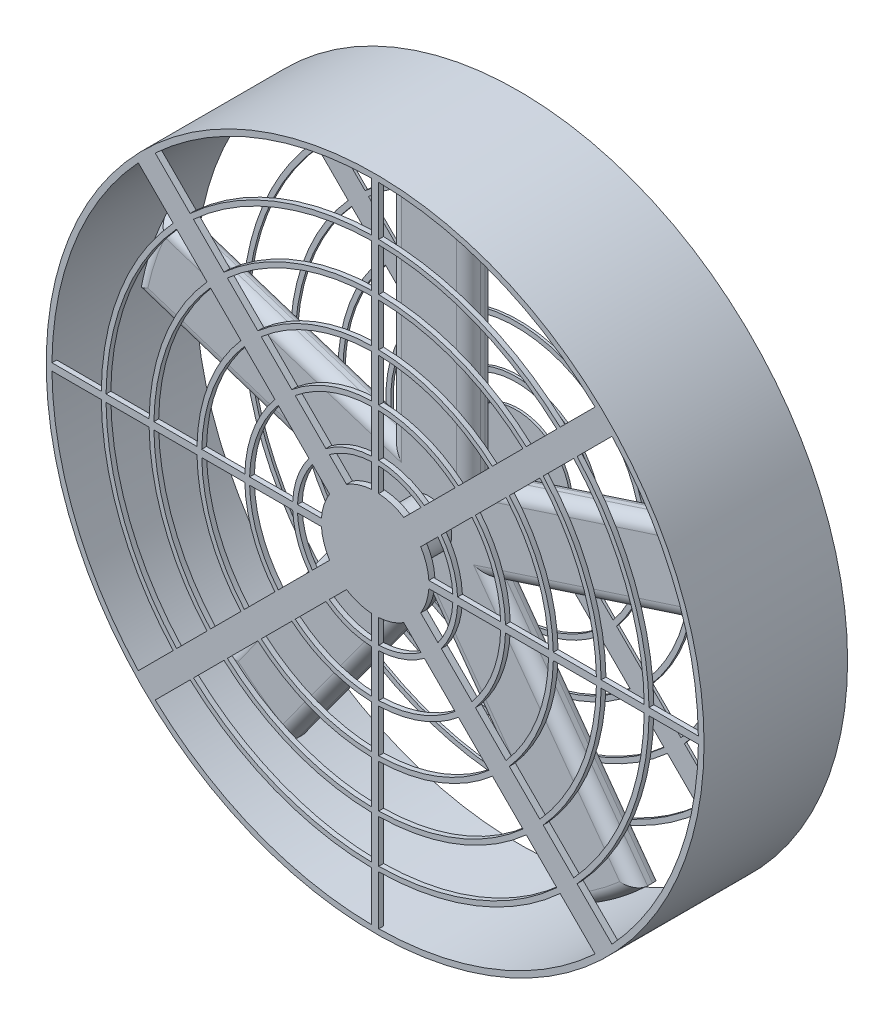
SolidWorks part; units mm, degrees
ref_plane "Alzado" through (0, 0, 0) normal (0, 0, 1) x (1, 0, 0)
ref_plane "Planta" through (0, 0, 0) normal (0, 1, 0) x (1, 0, 0)
ref_plane "Vista lateral" through (0, 0, 0) normal (1, 0, 0) x (0, 0, -1)
sketch "Croquis1" plane through (0, 0, 0) normal (0, 0, 1) x (1, 0, 0)
  circle A0 centre (0, 0) radius 275
  circle A1 centre (0, 0) radius 270.2375
  dimension "D1" = 550
  dimension "D2" = 4.7625
extrude "Saliente-Extruir1" add sketch "Croquis1" along normal blind 120
sketch "Croquis2" plane through (0, 0, 120) normal (0, 0, 1) x (1, 0, 0)
  line L0 (0, 270.2375) -> (0, 0) construction
  line L1 (0, 0) -> (270.2375, 0) construction
  line L2 (0, 0) -> (191.0868, 191.0868) construction
  line L3 (0, 14.1421) -> (185.2495, 199.3916)
  line L4 (14.1421, 0) -> (199.3916, 185.2495)
  line L5 (-14.1421, 0) -> (-199.3916, 185.2495)
  line L6 (0, 14.1421) -> (-185.2495, 199.3916)
  line L7 (0, 0) -> (191.0868, -191.0868) construction
  line L8 (0, -14.1421) -> (-185.2495, -199.3916)
  line L9 (-14.1421, 0) -> (-199.3916, -185.2495)
  line L10 (14.1421, 0) -> (199.3916, -185.2495)
  line L11 (0, -14.1421) -> (185.2495, -199.3916)
  circle A0 centre (0, 0) radius 270.2375 construction
  arc A1 (185.2495, 199.3916) -> (199.3916, 185.2495) centre (0, 0) cw
  arc A2 (-185.2495, 199.3916) -> (-199.3916, 185.2495) centre (0, 0) ccw
  arc A3 (-185.2495, -199.3916) -> (-199.3916, -185.2495) centre (0, 0) cw
  arc A4 (185.2495, -199.3916) -> (199.3916, -185.2495) centre (0, 0) ccw
  dimension "D1" = 10
  dimension "D2" = 10
extrude "Saliente-Extruir2" add sketch "Croquis2" against normal blind 5
sketch "Croquis3" plane through (0, 0, 115) normal (0, 0, -1) x (-1, 0, 0)
  circle A0 centre (0, 0) radius 45
  dimension "D1" = 90
extrude "Saliente-Extruir3" add sketch "Croquis3" against normal up to surface (5 mm away) up to face at (160.8022, 0, 120)
sketch "Croquis5" plane through (0, 0, 115) normal (0, 0, -1) x (-1, 0, 0)
  circle A0 centre (0, 0) radius 19.05
  dimension "D1" = 38.1
extrude "Saliente-Extruir4" add sketch "Croquis5" along normal blind 40
sketch "Croquis6" plane through (0, 0, 75) normal (0, 0, -1) x (-1, 0, 0)
  line L0 (0, 0) -> (0, 270.2375) construction
  line L1 (-33, 0) -> (-33, 248.5919)
  line L2 (33, 0) -> (33, 248.5919)
  line L3 (0, 0) -> (-33, 0)
  line L4 (0, 0) -> (33, 0)
  circle A0 centre (0, 0) radius 270.2375 construction
  arc A2 (33, 248.5919) -> (-33, 248.5919) centre (0, 0) ccw
  circle M8 centre (0, 0) radius 19.05
  dimension "D1" = 33
  dimension "D2" = 33
extrude "Saliente-Extruir5" add sketch "Croquis6" along normal blind 20 contours L0 A2 L1 L3 M8 | L0 L4 M8 | L3 L0 M8 | L0 L4 L2 A2 M8
pattern_circular "MatrizC1" count 5 every 72 about axis through (0, 0, 0) along (0, 0, 1) of "Saliente-Extruir5"
fillet "Redondeo1" radius 10 3 edges at (-33, 147.0063, 75) (0, 250.7727, 75) (33, 147.0063, 75)
fillet "Redondeo2" radius 10 12 edges at (-124.6137, 75.1877, 75) (-238.499, 77.493, 75) (-150.0088, 14.0426, 75) (-113.1057, -99.5337, 75) (-147.4005, -202.8794, 75) (-59.7106, -138.3275, 75) (59.7106, -138.3275, 75) (147.4005, -202.8794, 75) (113.1057, -99.5337, 75) (150.0088, 14.0426, 75) (238.499, 77.493, 75) (124.6137, 75.1877, 75)
sketch "Croquis7" plane through (0, 0, 120) normal (0, 0, 1) x (1, 0, 0)
  line L0 (0, 0) -> (0, 270.2375) construction
  line L1 (-3, 44.8999) -> (-3, 270.2208)
  line L2 (3, 44.8999) -> (3, 270.2208)
  arc A0 (183.8848, 198.027) -> (-183.8848, 198.027) centre (0, 0) ccw construction
  arc A1 (-3, 44.8999) -> (3, 44.8999) centre (0, 0) cw
  arc A3 (-3, 270.2208) -> (3, 270.2208) centre (0, 0) cw
  dimension "D1" = 3
  dimension "D2" = 3
extrude "Saliente-Extruir6" add sketch "Croquis7" against normal blind 4
pattern_circular "MatrizC2" count 4 every 90 about axis through (0, 0, 0) along (0, 0, 1) of "Saliente-Extruir6"
sketch "Croquis8" plane through (0, 0, 120) normal (0, 0, 1) x (1, 0, 0)
  circle A0 centre (0, 0) radius 65
  circle A1 centre (0, 0) radius 69
  circle A2 centre (0, 0) radius 105
  circle A3 centre (0, 0) radius 109
  circle A4 centre (0, 0) radius 145
  circle A5 centre (0, 0) radius 149
  circle A6 centre (0, 0) radius 185
  circle A7 centre (0, 0) radius 189
  circle A8 centre (0, 0) radius 225
  circle A9 centre (0, 0) radius 229
  line M2 (270.2208, 3) -> (44.8999, 3)
  line M4 (38.0953, 23.9531) -> (198.027, 183.8848)
  line M6 (3, -270.2208) -> (3, -44.8999)
  line M8 (23.9531, -38.0953) -> (183.8848, -198.027)
  line M10 (-270.2208, -3) -> (-44.8999, -3)
  line M12 (-38.0953, -23.9531) -> (-198.027, -183.8848)
  line M14 (-3, 270.2208) -> (-3, 44.8999)
  line M16 (-23.9531, 38.0953) -> (-183.8848, 198.027)
  line M17 (183.8848, 198.027) -> (23.9531, 38.0953)
  line M19 (3, 44.8999) -> (3, 270.2208)
  line M21 (-198.027, 183.8848) -> (-38.0953, 23.9531)
  line M23 (-44.8999, 3) -> (-270.2208, 3)
  line M25 (-183.8848, -198.027) -> (-23.9531, -38.0953)
  line M27 (-3, -44.8999) -> (-3, -270.2208)
  line M29 (44.8999, -3) -> (270.2208, -3)
  line M31 (198.027, -183.8848) -> (38.0953, -23.9531)
  dimension "D1" = 130
  dimension "D3" = 210
  dimension "D5" = 290
  dimension "D7" = 370
  dimension "D9" = 450
  dimension "D2" = 4
  dimension "D4" = 4
  dimension "D6" = 4
  dimension "D8" = 4
  dimension "D10" = 4
extrude "Saliente-Extruir7" add sketch "Croquis8" against normal blind 4 contours A1 A0 M14 M16 | A1 A0 M19 M14 | A1 A0 M17 M19 | A1 A0 M16 M21 | A1 A0 M4 M17 | A1 A0 M2 M4 | A1 A0 M29 M2 | A1 A0 M31 M29 | A1 A0 M8 M31 | A1 A0 M6 M8 | A1 A0 M27 M6 | A1 A0 M25 M27 | A1 A0 M12 M25 | A1 A0 M10 M12 | A1 A0 M23 M10 | A1 A0 M21 M23 | A3 A2 M16 M21 | A3 A2 M21 M23 | A3 A2 M14 M16 | A3 A2 M17 M19 | A3 A2 M19 M14 | A3 A2 M4 M17 | A3 A2 M2 M4 | A3 A2 M29 M2 | A3 A2 M31 M29 | A3 A2 M8 M31 | A3 A2 M6 M8 | A3 A2 M27 M6 | A3 A2 M25 M27 | A3 A2 M12 M25 | A3 A2 M10 M12 | A3 A2 M23 M10 | A5 A4 M23 M10 | A5 A4 M21 M23 | A5 A4 M10 M12 | A5 A4 M16 M21 | A5 A4 M14 M16 | A5 A4 M19 M14 | A5 A4 M17 M19 | A5 A4 M4 M17 | A5 A4 M2 M4 | A5 A4 M29 M2 | A5 A4 M31 M29 | A5 A4 M8 M31 | A5 A4 M6 M8 | A5 A4 M27 M6 | A5 A4 M25 M27 | A5 A4 M12 M25 | A7 A6 M12 M25 | A7 A6 M10 M12 | A7 A6 M25 M27 | A7 A6 M27 M6 | A7 A6 M6 M8 | A7 A6 M8 M31 | A7 A6 M31 M29 | A7 A6 M29 M2 | A7 A6 M2 M4 | A7 A6 M4 M17 | A7 A6 M17 M19 | A7 A6 M19 M14 | A7 A6 M14 M16 | A7 A6 M16 M21 | A7 A6 M21 M23 | A7 A6 M23 M10 | A9 A8 M23 M10 | A9 A8 M21 M23 | A9 A8 M10 M12 | A9 A8 M12 M25 | A9 A8 M25 M27 | A9 A8 M27 M6 | A9 A8 M6 M8 | A9 A8 M8 M31 | A9 A8 M31 M29 | A9 A8 M2 M4 | A9 A8 M4 M17 | A9 A8 M17 M19 | A9 A8 M19 M14 | A9 A8 M14 M16 | A9 A8 M16 M21
fillet "Redondeo3" radius 6 10 edges at (113.1057, -99.5337, 55) (150.0088, 14.0426, 55) (-59.7106, -138.3275, 55) (59.7106, -138.3275, 55) (-113.1057, -99.5337, 55) (-150.0088, 14.0426, 55) (-129.6137, 76.8123, 55) (-33, 147.0063, 55) (129.6137, 76.8123, 55) (33, 147.0063, 55)
sketch "Croquis9" plane through (0, 0, 0) normal (0, 0, -1) x (-1, 0, 0)
  circle A0 centre (0, 0) radius 270.2375
extrude "Saliente-Extruir8" add sketch "Croquis9" against normal blind 2 separate body
sketch "Croquis10" plane through (0, 0, 0) normal (0, 0, -1) x (-1, 0, 0)
  line L0 (-198.027, 183.8848) -> (-168.8441, 154.7019)
  line L1 (-183.8848, 198.027) -> (-154.7019, 168.8441)
  line L2 (-166.0129, 151.8707) -> (-140.5271, 126.3849)
  line L3 (-151.8707, 166.0129) -> (-126.3849, 140.5271)
  line L4 (-137.6946, 123.5524) -> (-112.1924, 98.0503)
  line L5 (-123.5524, 137.6946) -> (-98.0503, 112.1924)
  line L6 (-95.2153, 109.3574) -> (-69.6785, 83.8207)
  line L7 (-109.3574, 95.2153) -> (-83.8207, 69.6785)
  line L8 (-66.8377, 80.9798) -> (-41.2042, 55.3463)
  line L9 (-80.9798, 66.8377) -> (-55.3463, 41.2042)
  line L10 (-38.3437, 52.4858) -> (-23.9531, 38.0953)
  line L11 (-52.4858, 38.3437) -> (-38.0953, 23.9531)
  line L12 (183.8848, 198.027) -> (154.7019, 168.8441)
  line L13 (198.027, 183.8848) -> (168.8441, 154.7019)
  line L14 (198.027, -183.8848) -> (140.5271, -126.3849)
  line L15 (183.8848, -198.027) -> (126.3849, -140.5271)
  line L16 (-183.8848, -198.027) -> (-154.7019, -168.8441)
  line L17 (-198.027, -183.8848) -> (-168.8441, -154.7019)
  line L18 (-166.0129, -151.8707) -> (-140.5271, -126.3849)
  line L19 (-151.8707, -166.0129) -> (-126.3849, -140.5271)
  line L20 (-137.6946, -123.5524) -> (-112.1924, -98.0503)
  line L21 (-123.5524, -137.6946) -> (-98.0503, -112.1924)
  line L22 (-109.3574, -95.2153) -> (-83.8207, -69.6785)
  line L23 (-95.2153, -109.3574) -> (-69.6785, -83.8207)
  line L24 (-80.9798, -66.8377) -> (-55.3463, -41.2042)
  line L25 (-66.8377, -80.9798) -> (-41.2042, -55.3463)
  line L26 (-52.4858, -38.3437) -> (-38.0953, -23.9531)
  line L27 (-38.3437, -52.4858) -> (-23.9531, -38.0953)
  line L28 (137.6946, -123.5524) -> (112.1924, -98.0503)
  line L29 (123.5524, -137.6946) -> (98.0503, -112.1924)
  line L30 (109.3574, -95.2153) -> (83.8207, -69.6785)
  line L31 (95.2153, -109.3574) -> (69.6785, -83.8207)
  line L32 (80.9798, -66.8377) -> (55.3463, -41.2042)
  line L33 (66.8377, -80.9798) -> (41.2042, -55.3463)
  line L34 (52.4858, -38.3437) -> (38.0953, -23.9531)
  line L35 (38.3437, -52.4858) -> (23.9531, -38.0953)
  line L36 (38.3437, 52.4858) -> (23.9531, 38.0953)
  line L37 (52.4858, 38.3437) -> (38.0953, 23.9531)
  line L38 (66.8377, 80.9798) -> (41.2042, 55.3463)
  line L39 (80.9798, 66.8377) -> (55.3463, 41.2042)
  line L40 (95.2153, 109.3574) -> (69.6785, 83.8207)
  line L41 (109.3574, 95.2153) -> (83.8207, 69.6785)
  line L42 (123.5524, 137.6946) -> (98.0503, 112.1924)
  line L43 (137.6946, 123.5524) -> (112.1924, 98.0503)
  line L44 (151.8707, 166.0129) -> (126.3849, 140.5271)
  line L45 (166.0129, 151.8707) -> (140.5271, 126.3849)
  arc A0 (-52.4858, 38.3437) -> (-52.4858, -38.3437) centre (0, 0) ccw
  arc A1 (-55.3463, 41.2042) -> (-55.3463, -41.2042) centre (0, 0) ccw
  arc A2 (-80.9798, 66.8377) -> (-80.9798, -66.8377) centre (0, 0) ccw
  arc A3 (-83.8207, 69.6785) -> (-83.8207, -69.6785) centre (0, 0) ccw
  arc A4 (-109.3574, 95.2153) -> (-109.3574, -95.2153) centre (0, 0) ccw
  arc A5 (-112.1924, 98.0503) -> (-112.1924, -98.0503) centre (0, 0) ccw
  arc A6 (-137.6946, 123.5524) -> (-137.6946, -123.5524) centre (0, 0) ccw
  arc A7 (-140.5271, 126.3849) -> (-140.5271, -126.3849) centre (0, 0) ccw
  arc A8 (-166.0129, 151.8707) -> (-166.0129, -151.8707) centre (0, 0) ccw
  arc A9 (-168.8441, 154.7019) -> (-168.8441, -154.7019) centre (0, 0) ccw
  arc A10 (-154.7019, -168.8441) -> (154.7019, -168.8441) centre (0, 0) ccw
  arc A11 (-151.8707, -166.0129) -> (151.8707, -166.0129) centre (0, 0) ccw
  arc A12 (-123.5524, -137.6946) -> (123.5524, -137.6946) centre (0, 0) ccw
  arc A13 (-126.3849, -140.5271) -> (126.3849, -140.5271) centre (0, 0) ccw
  arc A14 (-95.2153, -109.3574) -> (95.2153, -109.3574) centre (0, 0) ccw
  arc A15 (-98.0503, -112.1924) -> (98.0503, -112.1924) centre (0, 0) ccw
  arc A16 (-66.8377, -80.9798) -> (66.8377, -80.9798) centre (0, 0) ccw
  arc A17 (-69.6785, -83.8207) -> (69.6785, -83.8207) centre (0, 0) ccw
  arc A18 (-38.3437, -52.4858) -> (38.3437, -52.4858) centre (0, 0) ccw
  arc A19 (-41.2042, -55.3463) -> (41.2042, -55.3463) centre (0, 0) ccw
  arc A20 (-23.9531, -38.0953) -> (23.9531, -38.0953) centre (0, 0) ccw
  arc A21 (-38.0953, 23.9531) -> (-38.0953, -23.9531) centre (0, 0) ccw
  arc A22 (23.9531, 38.0953) -> (-23.9531, 38.0953) centre (0, 0) ccw
  arc A23 (38.0953, -23.9531) -> (38.0953, 23.9531) centre (0, 0) ccw
  arc A24 (52.4858, -38.3437) -> (52.4858, 38.3437) centre (0, 0) ccw
  arc A25 (55.3463, -41.2042) -> (55.3463, 41.2042) centre (0, 0) ccw
  arc A26 (80.9798, -66.8377) -> (80.9798, 66.8377) centre (0, 0) ccw
  arc A27 (83.8207, -69.6785) -> (83.8207, 69.6785) centre (0, 0) ccw
  arc A28 (109.3574, -95.2153) -> (109.3574, 95.2153) centre (0, 0) ccw
  arc A29 (112.1924, -98.0503) -> (112.1924, 98.0503) centre (0, 0) ccw
  arc A30 (137.6946, -123.5524) -> (137.6946, 123.5524) centre (0, 0) ccw
  arc A31 (140.5271, -126.3849) -> (140.5271, 126.3849) centre (0, 0) ccw
  arc A32 (166.0129, -151.8707) -> (166.0129, 151.8707) centre (0, 0) ccw
  arc A33 (168.8441, -154.7019) -> (168.8441, 154.7019) centre (0, 0) ccw
  arc A34 (41.2042, 55.3463) -> (-41.2042, 55.3463) centre (0, 0) ccw
  arc A35 (38.3437, 52.4858) -> (-38.3437, 52.4858) centre (0, 0) ccw
  arc A36 (69.6785, 83.8207) -> (-69.6785, 83.8207) centre (0, 0) ccw
  arc A37 (66.8377, 80.9798) -> (-66.8377, 80.9798) centre (0, 0) ccw
  arc A38 (98.0503, 112.1924) -> (-98.0503, 112.1924) centre (0, 0) ccw
  arc A39 (95.2153, 109.3574) -> (-95.2153, 109.3574) centre (0, 0) ccw
  arc A40 (126.3849, 140.5271) -> (-126.3849, 140.5271) centre (0, 0) ccw
  arc A41 (123.5524, 137.6946) -> (-123.5524, 137.6946) centre (0, 0) ccw
  arc A42 (154.7019, 168.8441) -> (-154.7019, 168.8441) centre (0, 0) ccw
  arc A43 (151.8707, 166.0129) -> (-151.8707, 166.0129) centre (0, 0) ccw
  arc A45 (183.8848, 198.027) -> (-183.8848, 198.027) centre (0, 0) ccw
  arc A46 (198.027, -183.8848) -> (198.027, 183.8848) centre (0, 0) ccw
  arc A47 (-183.8848, -198.027) -> (183.8848, -198.027) centre (0, 0) ccw
  arc A48 (-198.027, 183.8848) -> (-198.027, -183.8848) centre (0, 0) ccw
  circle M1 centre (0, 0) radius 270.2375
extrude "Cortar-Extruir1" cut sketch "Croquis10" against normal blind 10 contours A9 L0 L17 M1 | L2 A8 L18 A7 | L4 A6 L20 A5 | L7 A4 L22 A3 | L9 A2 L24 A1 | A21 L11 A0 L26 | A20 L27 A18 L35 | A19 L25 A16 L33 | A17 L23 A14 L31 | A15 L21 A12 L29 | A13 L19 A11 L15 | A10 L16 L15 M1 | A33 L14 L13 M1 | L14 A32 L45 A31 | L28 A30 L43 A29 | L30 A28 L41 A27 | L32 A26 L39 A25 | A42 L12 L1 M1 | L44 A43 L3 A40 | L42 A41 L5 A38 | L40 A39 L6 A36 | L38 A37 L8 A34 | L36 A35 L10 A22 | L34 A24 L37 A23
